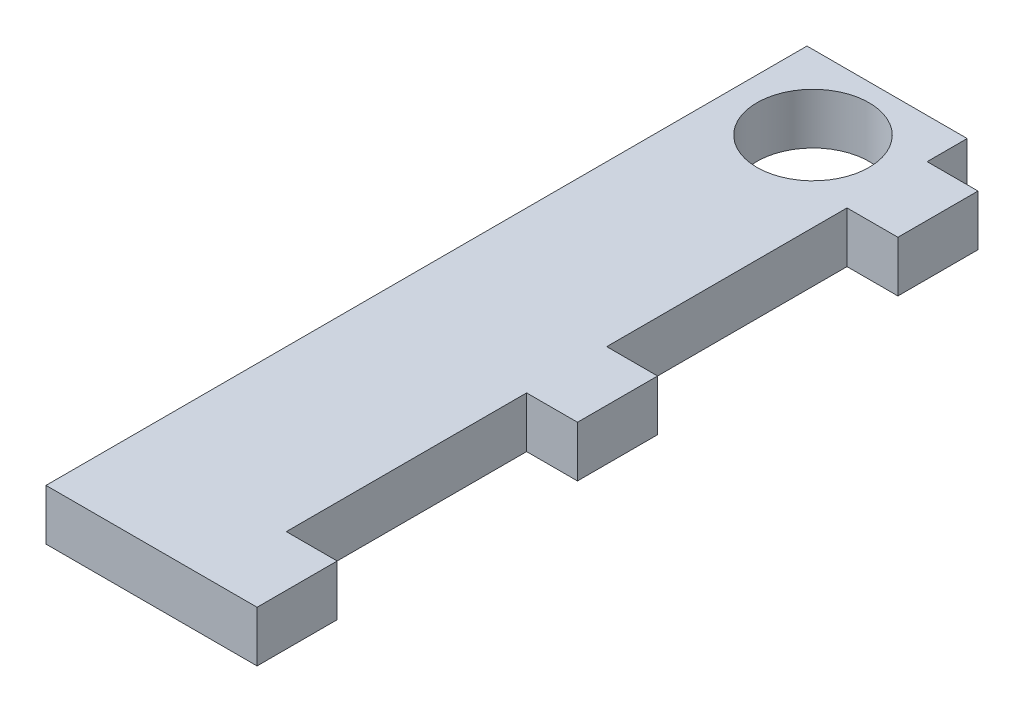
SolidWorks part; units mm, degrees
ref_plane "Front Plane" through (0, 0, 0) normal (0, 0, 1) x (1, 0, 0)
ref_plane "Top Plane" through (0, 0, 0) normal (0, 1, 0) x (1, 0, 0)
ref_plane "Right Plane" through (0, 0, 0) normal (1, 0, 0) x (0, 0, -1)
other "Default"
sketch "Sketch1" plane through (0, 0, 0) normal (0, 1, 0) x (1, 0, 0)
  line L0 (-13.175, 47.5) -> (-13.175, -47.5)
  line L1 (-13.175, -47.5) -> (13.175, -47.5)
  line L2 (13.175, -47.5) -> (13.175, -37.5)
  line L3 (13.175, -37.5) -> (6.825, -37.5)
  line L4 (6.825, -37.5) -> (6.825, -7.5)
  line L5 (6.825, -7.5) -> (13.175, -7.5)
  line L6 (13.175, -7.5) -> (13.175, 2.5)
  line L7 (13.175, 2.5) -> (6.825, 2.5)
  line L8 (6.825, 2.5) -> (6.825, 32.5)
  line L9 (6.825, 32.5) -> (13.175, 32.5)
  line L10 (13.175, 32.5) -> (13.175, 42.5)
  line L12 (-13.175, 47.5) -> (13.175, -47.5) construction
  line L13 (13.175, 42.5) -> (6.825, 42.5)
  line L14 (6.825, 42.5) -> (6.825, 47.5)
  line L15 (6.825, 47.5) -> (-13.175, 47.5)
  circle A0 centre (-3.175, 38.25) radius 7
  point P8 (0, 0)
  point P15 (0, 0)
  point P18 (0, 0)
  point P21 (-3.175, 47.5)
  point P22 (0, 0)
  point P23 (0, 0)
  point P24 (-13.175, 44.6304)
  dimension "D5" = 14
  dimension "D1" = 10
  dimension "D2" = 5
  dimension "D3" = 20
  dimension "D4" = 6.35
  dimension "D6" = 4.25
  dimension "D7" = 90
extrude "Boss-Extrude1" add sketch "Sketch1" along normal mid plane 6.35
sketch "Sketch2" plane through (0, 3.175, 0) normal (0, 1, 0) x (1, 0, 0)
  line L0 (13.175, -47.5) -> (13.175, -37.5) construction
  line L1 (-13.175, -47.5) -> (13.175, -47.5)
  line L2 (-13.175, -47.5) -> (-13.175, 7)
  line L3 (-13.175, 7) -> (13.175, 7)
  line L4 (13.175, -47.5) -> (13.175, 7)
  line L5 (13.175, 42.5) -> (6.825, 42.5) construction
  point P5 (0, 0)
  point P6 (0, 0)
  point P7 (0, 0)
  dimension "D1" = 35.5
extrude "Short" [suppressed] cut sketch "Sketch2" against normal through all
sketch "Sketch3" [suppressed] plane through (0, 3.175, 0) normal (0, 1, 0) x (1, 0, 0)
  line L0 (13.175, 32.5) -> (13.175, 42.5) construction
  line L1 (6.825, 7) -> (13.175, 7)
  line L2 (6.825, 7) -> (6.825, 17)
  line L3 (6.825, 17) -> (13.175, 17)
  line L4 (13.175, 7) -> (13.175, 17)
extrude "Short Tab" [suppressed] add sketch "Sketch3" against normal through all
